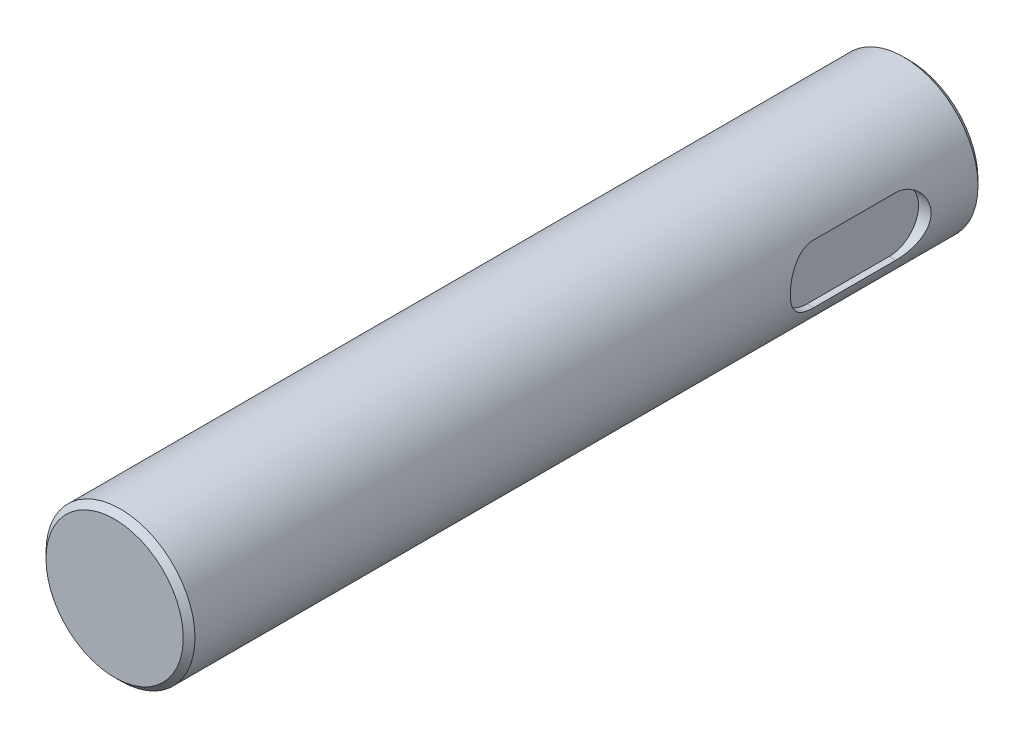
SolidWorks part; units mm, degrees
ref_plane "Спереди" through (0, 0, 0) normal (0, 0, 1) x (1, 0, 0)
ref_plane "Сверху" through (0, 0, 0) normal (0, 1, 0) x (1, 0, 0)
ref_plane "Справа" through (0, 0, 0) normal (1, 0, 0) x (0, 0, -1)
sketch "Эскиз1" plane through (0, 0, 0) normal (1, 0, 0) x (0, 0, -1)
  line L0 (0, 0) -> (0, 6.35)
  line L1 (0, 6.35) -> (67.75, 6.35)
  line L6 (0, 0) -> (67.75, 0)
  line L7 (67.75, 0) -> (67.75, 6.35)
  dimension "D1" = 6.35
  dimension "D2" = 67.75
revolve "Повернуть1" add sketch "Эскиз1" angle 360 about L6
chamfer "Фаска1" distance 0.5 angle 45 2 edges at (6.35, 0, -67.75) (6.35, 0, 0)
ref_plane "Плоскость1" through (6.35, 0, 0) normal (1, 0, 0) x (0, 0, -1)
sketch "Эскиз2" plane through (6.35, 0, 0) normal (1, 0, 0) x (0, 0, -1)
  line L0 (53.75, 0) -> (60.75, 0) construction
  line L1 (53.75, 2.5) -> (60.75, 2.5)
  line L2 (53.75, -2.5) -> (60.75, -2.5)
  line L3 (67.75, -5.85) -> (67.75, 5.85) construction
  arc A0 (53.75, 2.5) -> (53.75, -2.5) centre (53.75, 0) ccw
  arc A1 (60.75, -2.5) -> (60.75, 2.5) centre (60.75, 0) ccw
  point P3 (57.25, 0)
  dimension "D2" = 7
  dimension "D3" = 7
  dimension "D1" = 5
extrude "Вырез-Вытянуть1" cut sketch "Эскиз2" against normal blind 1.075
